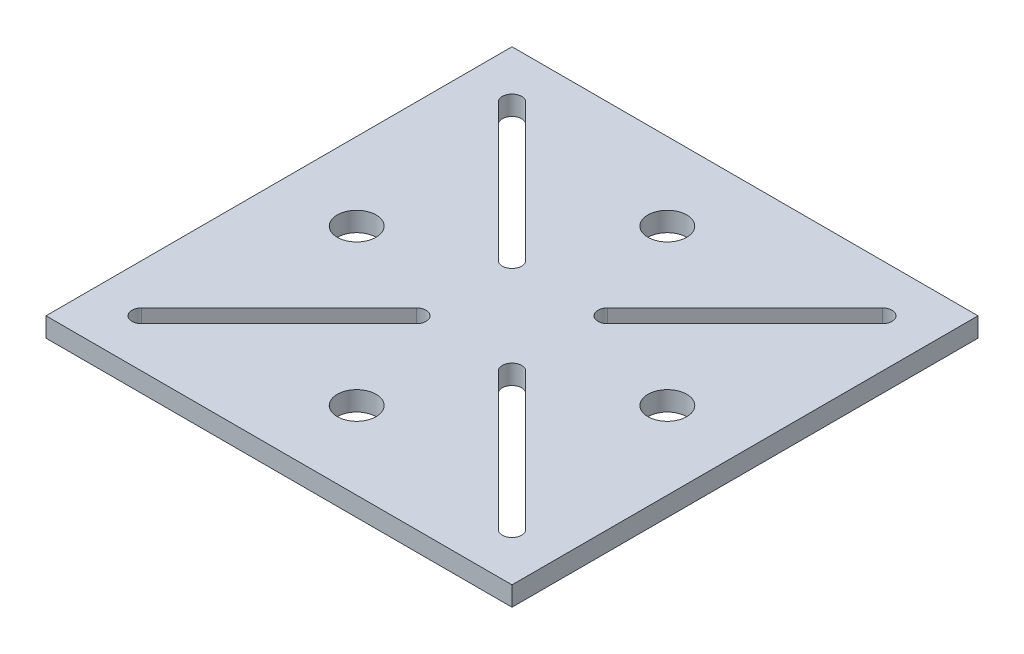
SolidWorks part; units mm, degrees
material "2024-T3"
ref_plane "Front Plane" through (0, 0, 0) normal (0, 0, 1) x (1, 0, 0)
ref_plane "Top Plane" through (0, 0, 0) normal (0, 1, 0) x (1, 0, 0)
ref_plane "Right Plane" through (0, 0, 0) normal (1, 0, 0) x (0, 0, -1)
sketch "Sketch1" plane through (0, 0, 0) normal (0, 1, 0) x (1, 0, 0)
  line L0 (0, 152.4) -> (152.4, 0) construction
  line L1 (0, 0) -> (152.4, 0)
  line L2 (0, 0) -> (0, 152.4)
  line L3 (0, 152.4) -> (152.4, 152.4)
  line L4 (152.4, 0) -> (152.4, 152.4)
  line L5 (76.2, 152.4) -> (76.2, 0) construction
  line L6 (136.7506, 136.7506) -> (91.8494, 91.8494) construction
  line L7 (15.6494, 136.7506) -> (60.5506, 91.8494) construction
  line L8 (17.8944, 138.9957) -> (62.7957, 94.0944)
  line L9 (13.4043, 134.5056) -> (58.3056, 89.6043)
  line L10 (0, 76.2) -> (152.4, 76.2) construction
  line L11 (134.5056, 138.9957) -> (89.6043, 94.0944)
  line L12 (138.9957, 134.5056) -> (94.0944, 89.6043)
  line L13 (136.7506, 15.6494) -> (91.8494, 60.5506) construction
  line L14 (134.5056, 13.4043) -> (89.6043, 58.3056)
  line L15 (138.9957, 17.8944) -> (94.0944, 62.7957)
  line L16 (15.6494, 15.6494) -> (60.5506, 60.5506) construction
  line L17 (17.8944, 13.4043) -> (62.7957, 58.3056)
  line L18 (13.4043, 17.8944) -> (58.3056, 62.7957)
  arc A0 (134.5056, 138.9957) -> (138.9957, 134.5056) centre (136.7506, 136.7506) cw
  arc A1 (94.0944, 89.6043) -> (89.6043, 94.0944) centre (91.8494, 91.8494) cw
  arc A2 (17.8944, 138.9957) -> (13.4043, 134.5056) centre (15.6494, 136.7506) ccw
  arc A3 (58.3056, 89.6043) -> (62.7957, 94.0944) centre (60.5506, 91.8494) ccw
  arc A4 (134.5056, 13.4043) -> (138.9957, 17.8944) centre (136.7506, 15.6494) ccw
  arc A5 (94.0944, 62.7957) -> (89.6043, 58.3056) centre (91.8494, 60.5506) ccw
  arc A6 (17.8944, 13.4043) -> (13.4043, 17.8944) centre (15.6494, 15.6494) cw
  arc A7 (58.3056, 62.7957) -> (62.7957, 58.3056) centre (60.5506, 60.5506) cw
  circle A8 centre (25.4, 76.2) radius 6.35
  circle A9 centre (76.2, 127) radius 6.35
  circle A10 centre (127, 76.2) radius 6.35
  circle A11 centre (76.2, 25.4) radius 6.35
  point P5 (76.2, 76.2)
  point P10 (114.3, 114.3)
  point P12 (38.1, 114.3)
  point P26 (114.3, 38.1)
  point P33 (38.1, 38.1)
  dimension "D2" = 3.175
  dimension "D5" = 12.7
  dimension "D1" = 152.4
  dimension "D3" = 63.5
  dimension "D4" = 38.1
  dimension "D6" = 50.8
  dimension "D7" = 50.8
  dimension "D8" = 50.8
  dimension "D9" = 50.8
extrude "Boss-Extrude1" add sketch "Sketch1" along normal blind 6.35
